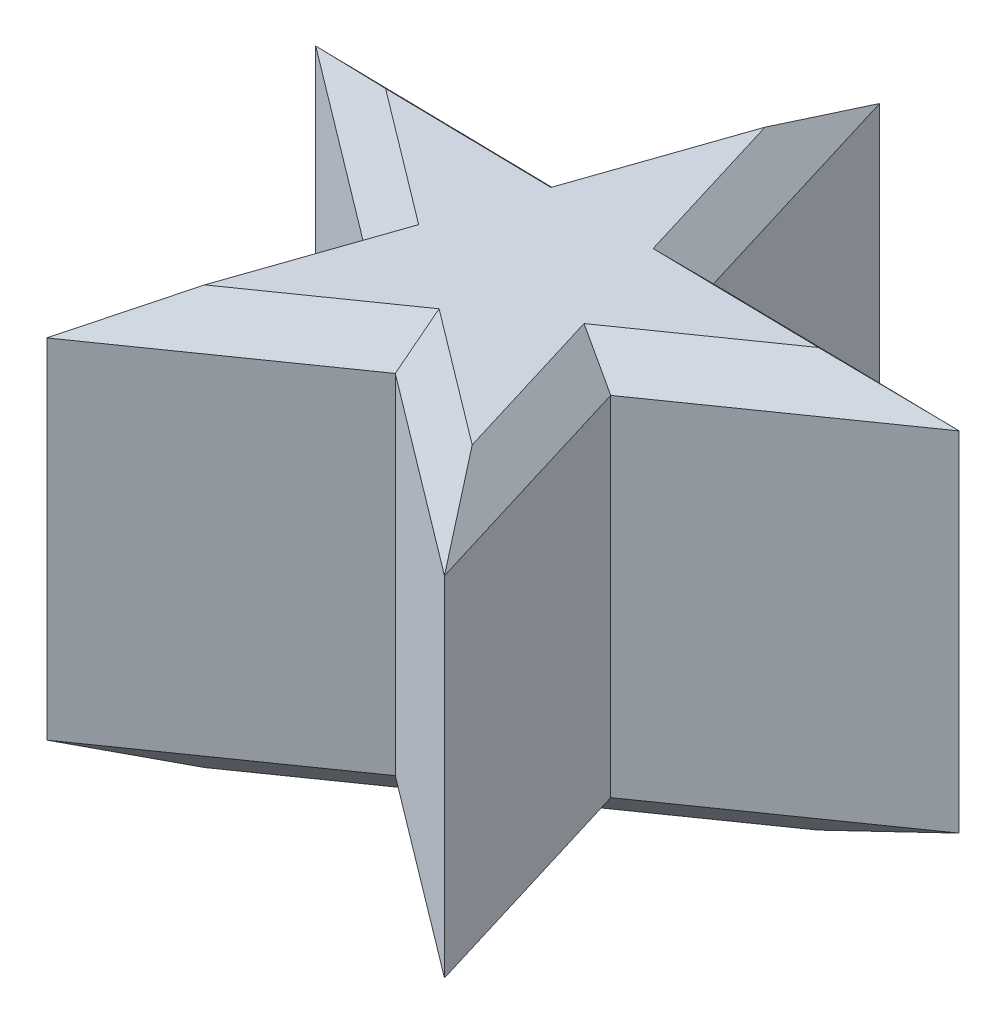
SolidWorks part; units mm, degrees
ref_plane "Front Plane" through (0, 0, 0) normal (0, 0, 1) x (1, 0, 0)
ref_plane "Top Plane" through (0, 0, 0) normal (0, 1, 0) x (1, 0, 0)
ref_plane "Right Plane" through (0, 0, 0) normal (1, 0, 0) x (0, 0, -1)
sketch "Sketch1" plane through (0, 0, 0) normal (0, 1, 0) x (1, 0, 0)
  line L0 (-4.6745, 1.6109) -> (-1.0828, 1.5473)
  line L1 (2.8349, -4.0508) -> (4.7286, 1.4444) construction
  line L2 (4.7286, 1.4444) -> (0.0875, 4.9435) construction
  line L3 (0.0875, 4.9435) -> (-4.6745, 1.6109) construction
  line L4 (-4.6745, 1.6109) -> (-2.9765, -3.9479) construction
  line L5 (-2.9765, -3.9479) -> (2.8349, -4.0508) construction
  line L6 (4.7286, 1.4444) -> (1.7855, -0.6153)
  line L7 (-2.9765, -3.9479) -> (-1.8062, -0.5517)
  line L8 (0.0875, 4.9435) -> (1.1369, 1.508)
  line L9 (2.8349, -4.0508) -> (-0.0334, -1.8882)
  line L10 (1.1369, 1.508) -> (4.7286, 1.4444)
  line L11 (-1.0828, 1.5473) -> (0.0875, 4.9435)
  line L12 (-1.8062, -0.5517) -> (-4.6745, 1.6109)
  line L13 (-0.0334, -1.8882) -> (-2.9765, -3.9479)
  line L14 (1.7855, -0.6153) -> (2.8349, -4.0508)
  circle A0 centre (0, 0) radius 4 construction
  dimension "D1" = 8
extrude "Boss-Extrude1" add sketch "Sketch1" along normal mid plane 6
chamfer "Chamfer1" distance 0.5 angle 45 20 edges at (-2.8787, -3, -1.5791) (-3.2403, -3, -0.5296) (-2.3913, -3, 2.2498) (-1.505, -3, 2.9181) (1.4007, -3, 2.9695) (2.3102, -3, 2.3331) (3.257, -3, -0.4146) (2.9328, -3, -1.4762) (0.6122, -3, -3.2257) (-0.4977, -3, -3.2454) (0.6122, 3, -3.2257) (2.9328, 3, -1.4762) (3.257, 3, -0.4146) (2.3102, 3, 2.3331) (1.4007, 3, 2.9695) (-1.505, 3, 2.9181) (-2.3913, 3, 2.2498) (-3.2403, 3, -0.5296) (-2.8787, 3, -1.5791) (-0.4977, 3, -3.2454)
